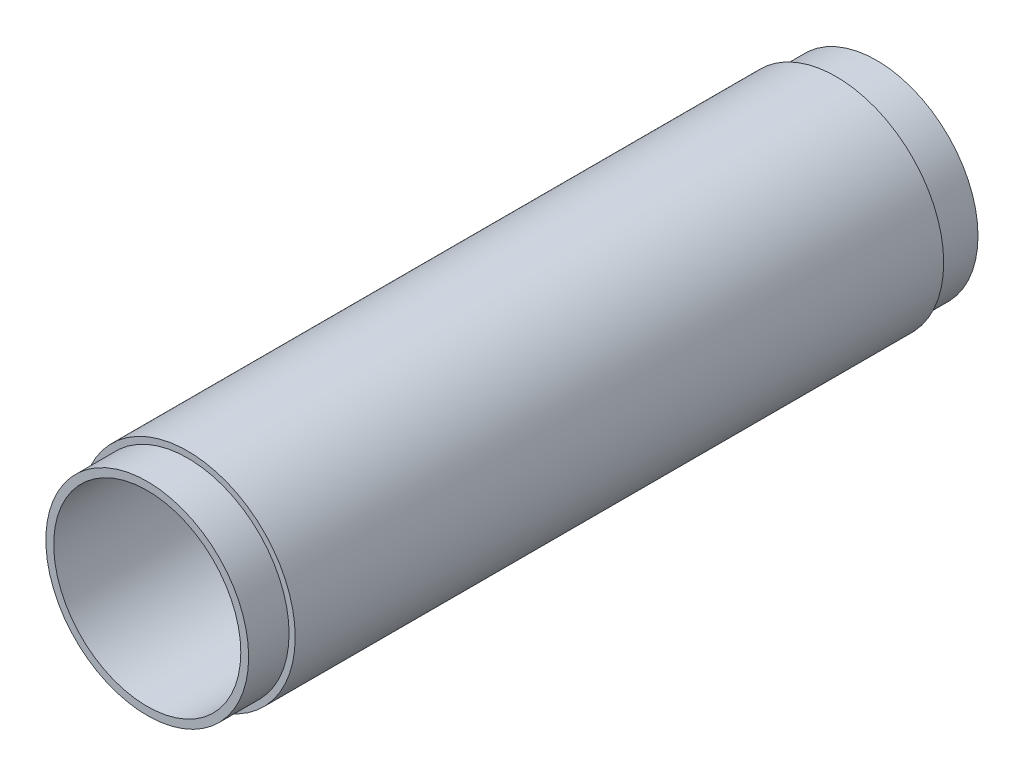
SolidWorks part; units mm, degrees
material "ASTM A36 Steel"
ref_plane "Front Plane" through (0, 0, 0) normal (0, 0, 1) x (1, 0, 0)
ref_plane "Top Plane" through (0, 0, 0) normal (0, 1, 0) x (1, 0, 0)
ref_plane "Right Plane" through (0, 0, 0) normal (1, 0, 0) x (0, 0, -1)
sketch "Sketch1" plane through (0, 0, 0) normal (1, 0, 0) x (0, 0, -1)
  line L0 (14.1067, 0) -> (88.9338, 0) construction
  line L1 (0, 11.049) -> (86.1441, 11.049)
  line L2 (86.1441, 11.049) -> (86.1441, 11.9761)
  line L3 (86.1441, 11.9761) -> (81.3689, 11.9761)
  line L4 (81.3689, 11.9761) -> (81.3689, 12.7)
  line L5 (81.3689, 12.7) -> (4.7752, 12.7)
  line L6 (4.7752, 12.7) -> (4.7752, 11.9761)
  line L7 (4.7752, 11.9761) -> (0, 11.9761)
  line L8 (0, 11.9761) -> (0, 11.049)
  dimension "D1" = 1.651
  dimension "D2" = 25.4
  dimension "D3" = 23.9522
  dimension "D4" = 4.7752
  dimension "D5" = 86.1441
  dimension "D6" = 4.7752
revolve "Revolve1" add sketch "Sketch1" angle 360 about L0
